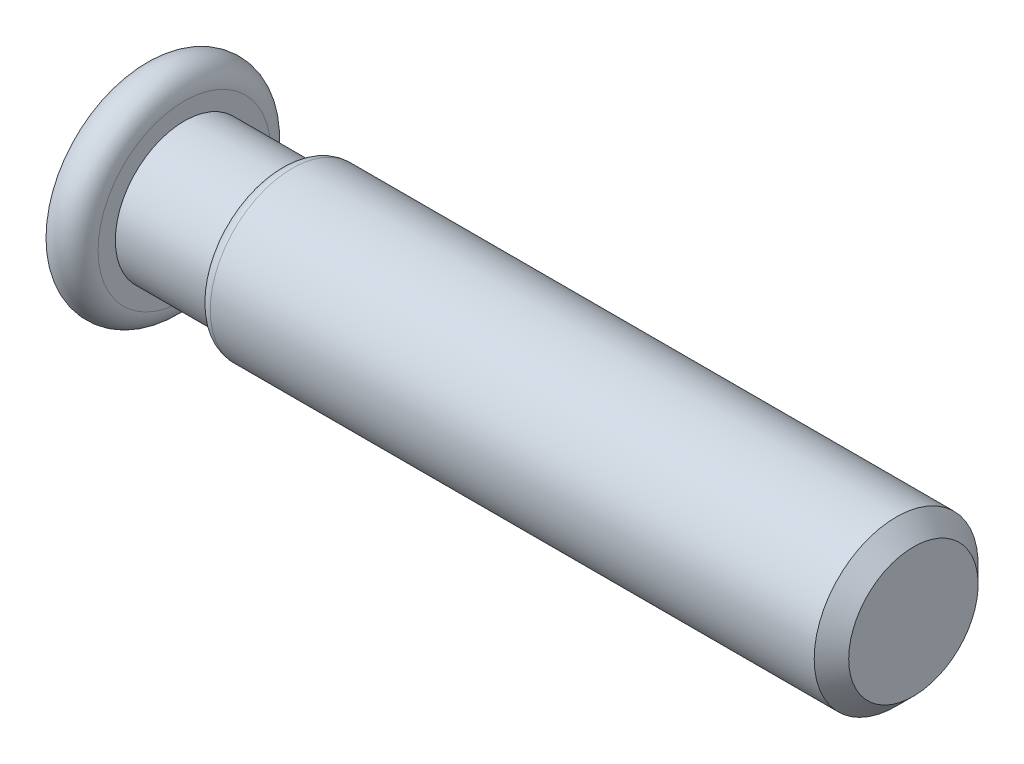
SolidWorks part; units mm, degrees
material "Glass"
ref_plane "Front Plane" through (0, 0, 0) normal (0, 0, 1) x (1, 0, 0)
ref_plane "Top Plane" through (0, 0, 0) normal (0, 1, 0) x (1, 0, 0)
ref_plane "Right Plane" through (0, 0, 0) normal (1, 0, 0) x (0, 0, -1)
sketch "Sketch1" plane through (0, 0, 0) normal (0, 0, 1) x (1, 0, 0)
  line L0 (0, 0) -> (0, 10)
  line L1 (5, 10) -> (5, 8)
  line L2 (5, 8) -> (16, 8)
  line L3 (17.5, 9.5) -> (87.5, 9.5)
  line L4 (87.5, 9.5) -> (89.5, 7.5)
  line L5 (89.5, 7.5) -> (89.5, 0)
  line L6 (0, 0) -> (89.5, 0)
  arc A0 (0, 10) -> (5, 10) centre (2.5, 10) cw
  arc A1 (16, 8) -> (17.5, 9.5) centre (17.5, 8) cw
  dimension "D4" = 2.5
  dimension "D7" = 1.5
  dimension "D1" = 70
  dimension "D2" = 2
  dimension "D3" = 9.5
  dimension "D5" = 10
  dimension "D6" = 11
  dimension "D8" = 45
revolve "Revolve1" add sketch "Sketch1" angle 360 about L6
